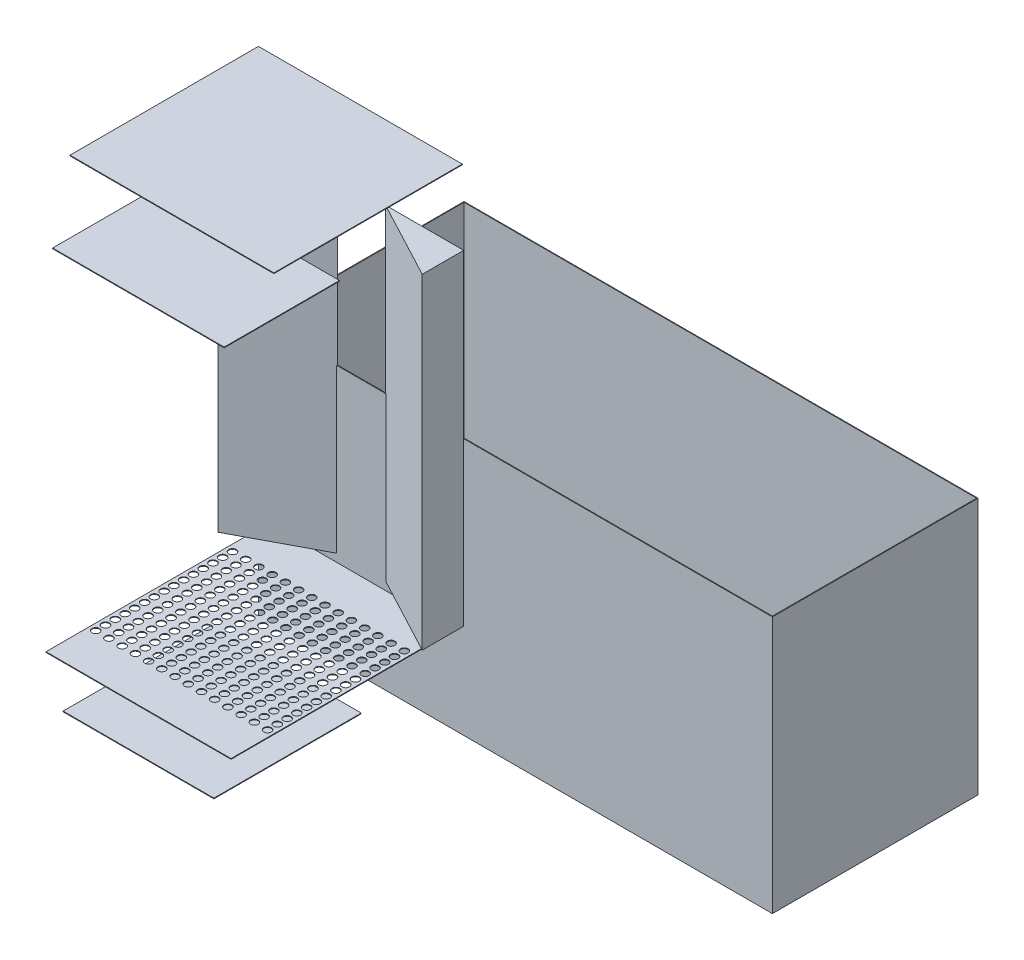
SolidWorks part; units mm, degrees
ref_plane "Спереди" through (0, 0, 0) normal (0, 0, 1) x (1, 0, 0)
ref_plane "Сверху" through (0, 0, 0) normal (0, 1, 0) x (1, 0, 0)
ref_plane "Справа" through (0, 0, 0) normal (1, 0, 0) x (0, 0, -1)
sketch "MASTER_FOOTPRINT" plane through (0, 0, 0) normal (0, 1, 0) x (1, 0, 0)
  line L1 (0, 0) -> (1500, 0)
  line L2 (0, 0) -> (0, 600)
  line L3 (0, 600) -> (1500, 600)
  line L4 (1500, 0) -> (1500, 600)
  dimension "D1" = 1500
  dimension "D2" = 600
extrude "BATH_BASE_PLATE" add sketch "MASTER_FOOTPRINT" along normal blind 750
shell "BATH_SHELL_2MM" thickness 2
sketch "Эскиз1" plane through (0, 0, 0) normal (0, 1, 0) x (1, 0, 0)
  line L1 (80, -220) -> (520, -220)
  line L2 (80, -220) -> (80, -650)
  line L3 (80, -650) -> (520, -650)
  line L4 (520, -220) -> (520, -650)
extrude "INLET_IMPACT_BAFFLE" add sketch "Эскиз1" along normal blind 2 from offset 125 separate body
sketch "Эскиз2" plane through (0, 0, 0) normal (0, 1, 0) x (1, 0, 0)
  line L0 (2, 2) -> (1498, 2) construction
  line L1 (30, 2) -> (570, 2)
  line L2 (30, 2) -> (30, -650)
  line L3 (30, -650) -> (570, -650)
  line L4 (570, 2) -> (570, -650)
  circle A0 centre (49.2857, -125) radius 11
  circle A1 centre (49.2857, -153.5) radius 11
  circle A2 centre (49.2857, -182) radius 11
  circle A3 centre (49.2857, -210.5) radius 11
  circle A4 centre (49.2857, -239) radius 11
  circle A5 centre (49.2857, -267.5) radius 11
  circle A6 centre (49.2857, -296) radius 11
  circle A7 centre (49.2857, -324.5) radius 11
  circle A8 centre (49.2857, -353) radius 11
  circle A9 centre (49.2857, -381.5) radius 11
  circle A10 centre (49.2857, -410) radius 11
  circle A11 centre (49.2857, -438.5) radius 11
  circle A12 centre (49.2857, -467) radius 11
  circle A13 centre (49.2857, -495.5) radius 11
  circle A14 centre (49.2857, -524) radius 11
  circle A15 centre (87.8571, -125) radius 11
  circle A16 centre (87.8571, -153.5) radius 11
  circle A17 centre (87.8571, -182) radius 11
  circle A18 centre (87.8571, -210.5) radius 11
  circle A19 centre (87.8571, -239) radius 11
  circle A20 centre (87.8571, -267.5) radius 11
  circle A21 centre (87.8571, -296) radius 11
  circle A22 centre (87.8571, -324.5) radius 11
  circle A23 centre (87.8571, -353) radius 11
  circle A24 centre (87.8571, -381.5) radius 11
  circle A25 centre (87.8571, -410) radius 11
  circle A26 centre (87.8571, -438.5) radius 11
  circle A27 centre (87.8571, -467) radius 11
  circle A28 centre (87.8571, -495.5) radius 11
  circle A29 centre (87.8571, -524) radius 11
  circle A30 centre (126.4286, -125) radius 11
  circle A31 centre (126.4286, -153.5) radius 11
  circle A32 centre (126.4286, -182) radius 11
  circle A33 centre (126.4286, -210.5) radius 11
  circle A34 centre (126.4286, -239) radius 11
  circle A35 centre (126.4286, -267.5) radius 11
  circle A36 centre (126.4286, -296) radius 11
  circle A37 centre (126.4286, -324.5) radius 11
  circle A38 centre (126.4286, -353) radius 11
  circle A39 centre (126.4286, -381.5) radius 11
  circle A40 centre (126.4286, -410) radius 11
  circle A41 centre (126.4286, -438.5) radius 11
  circle A42 centre (126.4286, -467) radius 11
  circle A43 centre (126.4286, -495.5) radius 11
  circle A44 centre (126.4286, -524) radius 11
  circle A45 centre (165, -125) radius 11
  circle A46 centre (165, -153.5) radius 11
  circle A47 centre (165, -182) radius 11
  circle A48 centre (165, -210.5) radius 11
  circle A49 centre (165, -239) radius 11
  circle A50 centre (165, -267.5) radius 11
  circle A51 centre (165, -296) radius 11
  circle A52 centre (165, -324.5) radius 11
  circle A53 centre (165, -353) radius 11
  circle A54 centre (165, -381.5) radius 11
  circle A55 centre (165, -410) radius 11
  circle A56 centre (165, -438.5) radius 11
  circle A57 centre (165, -467) radius 11
  circle A58 centre (165, -495.5) radius 11
  circle A59 centre (165, -524) radius 11
  circle A60 centre (203.5714, -125) radius 11
  circle A61 centre (203.5714, -153.5) radius 11
  circle A62 centre (203.5714, -182) radius 11
  circle A63 centre (203.5714, -210.5) radius 11
  circle A64 centre (203.5714, -239) radius 11
  circle A65 centre (203.5714, -267.5) radius 11
  circle A66 centre (203.5714, -296) radius 11
  circle A67 centre (203.5714, -324.5) radius 11
  circle A68 centre (203.5714, -353) radius 11
  circle A69 centre (203.5714, -381.5) radius 11
  circle A70 centre (203.5714, -410) radius 11
  circle A71 centre (203.5714, -438.5) radius 11
  circle A72 centre (203.5714, -467) radius 11
  circle A73 centre (203.5714, -495.5) radius 11
  circle A74 centre (203.5714, -524) radius 11
  circle A75 centre (242.1429, -125) radius 11
  circle A76 centre (242.1429, -153.5) radius 11
  circle A77 centre (242.1429, -182) radius 11
  circle A78 centre (242.1429, -210.5) radius 11
  circle A79 centre (242.1429, -239) radius 11
  circle A80 centre (242.1429, -267.5) radius 11
  circle A81 centre (242.1429, -296) radius 11
  circle A82 centre (242.1429, -324.5) radius 11
  circle A83 centre (242.1429, -353) radius 11
  circle A84 centre (242.1429, -381.5) radius 11
  circle A85 centre (242.1429, -410) radius 11
  circle A86 centre (242.1429, -438.5) radius 11
  circle A87 centre (242.1429, -467) radius 11
  circle A88 centre (242.1429, -495.5) radius 11
  circle A89 centre (242.1429, -524) radius 11
  circle A90 centre (280.7143, -125) radius 11
  circle A91 centre (280.7143, -153.5) radius 11
  circle A92 centre (280.7143, -182) radius 11
  circle A93 centre (280.7143, -210.5) radius 11
  circle A94 centre (280.7143, -239) radius 11
  circle A95 centre (280.7143, -267.5) radius 11
  circle A96 centre (280.7143, -296) radius 11
  circle A97 centre (280.7143, -324.5) radius 11
  circle A98 centre (280.7143, -353) radius 11
  circle A99 centre (280.7143, -381.5) radius 11
  circle A100 centre (280.7143, -410) radius 11
  circle A101 centre (280.7143, -438.5) radius 11
  circle A102 centre (280.7143, -467) radius 11
  circle A103 centre (280.7143, -495.5) radius 11
  circle A104 centre (280.7143, -524) radius 11
  circle A105 centre (319.2857, -125) radius 11
  circle A106 centre (319.2857, -153.5) radius 11
  circle A107 centre (319.2857, -182) radius 11
  circle A108 centre (319.2857, -210.5) radius 11
  circle A109 centre (319.2857, -239) radius 11
  circle A110 centre (319.2857, -267.5) radius 11
  circle A111 centre (319.2857, -296) radius 11
  circle A112 centre (319.2857, -324.5) radius 11
  circle A113 centre (319.2857, -353) radius 11
  circle A114 centre (319.2857, -381.5) radius 11
  circle A115 centre (319.2857, -410) radius 11
  circle A116 centre (319.2857, -438.5) radius 11
  circle A117 centre (319.2857, -467) radius 11
  circle A118 centre (319.2857, -495.5) radius 11
  circle A119 centre (319.2857, -524) radius 11
  circle A120 centre (357.8571, -125) radius 11
  circle A121 centre (357.8571, -153.5) radius 11
  circle A122 centre (357.8571, -182) radius 11
  circle A123 centre (357.8571, -210.5) radius 11
  circle A124 centre (357.8571, -239) radius 11
  circle A125 centre (357.8571, -267.5) radius 11
  circle A126 centre (357.8571, -296) radius 11
  circle A127 centre (357.8571, -324.5) radius 11
  circle A128 centre (357.8571, -353) radius 11
  circle A129 centre (357.8571, -381.5) radius 11
  circle A130 centre (357.8571, -410) radius 11
  circle A131 centre (357.8571, -438.5) radius 11
  circle A132 centre (357.8571, -467) radius 11
  circle A133 centre (357.8571, -495.5) radius 11
  circle A134 centre (357.8571, -524) radius 11
  circle A135 centre (396.4286, -125) radius 11
  circle A136 centre (396.4286, -153.5) radius 11
  circle A137 centre (396.4286, -182) radius 11
  circle A138 centre (396.4286, -210.5) radius 11
  circle A139 centre (396.4286, -239) radius 11
  circle A140 centre (396.4286, -267.5) radius 11
  circle A141 centre (396.4286, -296) radius 11
  circle A142 centre (396.4286, -324.5) radius 11
  circle A143 centre (396.4286, -353) radius 11
  circle A144 centre (396.4286, -381.5) radius 11
  circle A145 centre (396.4286, -410) radius 11
  circle A146 centre (396.4286, -438.5) radius 11
  circle A147 centre (396.4286, -467) radius 11
  circle A148 centre (396.4286, -495.5) radius 11
  circle A149 centre (396.4286, -524) radius 11
  circle A150 centre (435, -125) radius 11
  circle A151 centre (435, -153.5) radius 11
  circle A152 centre (435, -182) radius 11
  circle A153 centre (435, -210.5) radius 11
  circle A154 centre (435, -239) radius 11
  circle A155 centre (435, -267.5) radius 11
  circle A156 centre (435, -296) radius 11
  circle A157 centre (435, -324.5) radius 11
  circle A158 centre (435, -353) radius 11
  circle A159 centre (435, -381.5) radius 11
  circle A160 centre (435, -410) radius 11
  circle A161 centre (435, -438.5) radius 11
  circle A162 centre (435, -467) radius 11
  circle A163 centre (435, -495.5) radius 11
  circle A164 centre (435, -524) radius 11
  circle A165 centre (473.5714, -125) radius 11
  circle A166 centre (473.5714, -153.5) radius 11
  circle A167 centre (473.5714, -182) radius 11
  circle A168 centre (473.5714, -210.5) radius 11
  circle A169 centre (473.5714, -239) radius 11
  circle A170 centre (473.5714, -267.5) radius 11
  circle A171 centre (473.5714, -296) radius 11
  circle A172 centre (473.5714, -324.5) radius 11
  circle A173 centre (473.5714, -353) radius 11
  circle A174 centre (473.5714, -381.5) radius 11
  circle A175 centre (473.5714, -410) radius 11
  circle A176 centre (473.5714, -438.5) radius 11
  circle A177 centre (473.5714, -467) radius 11
  circle A178 centre (473.5714, -495.5) radius 11
  circle A179 centre (473.5714, -524) radius 11
  circle A180 centre (512.1429, -125) radius 11
  circle A181 centre (512.1429, -153.5) radius 11
  circle A182 centre (512.1429, -182) radius 11
  circle A183 centre (512.1429, -210.5) radius 11
  circle A184 centre (512.1429, -239) radius 11
  circle A185 centre (512.1429, -267.5) radius 11
  circle A186 centre (512.1429, -296) radius 11
  circle A187 centre (512.1429, -324.5) radius 11
  circle A188 centre (512.1429, -353) radius 11
  circle A189 centre (512.1429, -381.5) radius 11
  circle A190 centre (512.1429, -410) radius 11
  circle A191 centre (512.1429, -438.5) radius 11
  circle A192 centre (512.1429, -467) radius 11
  circle A193 centre (512.1429, -495.5) radius 11
  circle A194 centre (512.1429, -524) radius 11
  circle A195 centre (550.7143, -125) radius 11
  circle A196 centre (550.7143, -153.5) radius 11
  circle A197 centre (550.7143, -182) radius 11
  circle A198 centre (550.7143, -210.5) radius 11
  circle A199 centre (550.7143, -239) radius 11
  circle A200 centre (550.7143, -267.5) radius 11
  circle A201 centre (550.7143, -296) radius 11
  circle A202 centre (550.7143, -324.5) radius 11
  circle A203 centre (550.7143, -353) radius 11
  circle A204 centre (550.7143, -381.5) radius 11
  circle A205 centre (550.7143, -410) radius 11
  circle A206 centre (550.7143, -438.5) radius 11
  circle A207 centre (550.7143, -467) radius 11
  circle A208 centre (550.7143, -495.5) radius 11
  circle A209 centre (550.7143, -524) radius 11
extrude "DISTRIBUTOR_D22" add sketch "Эскиз2" along normal blind 2 from offset 250 separate body
sketch "Эскиз3" plane through (0, 0, 0) normal (0, 1, 0) x (1, 0, 0)
  line L0 (30, -650) -> (570, -650) construction
  line L1 (49.2857, -313.5) -> (550, -313.5)
  line L2 (49.2857, -313.5) -> (49.2857, -650)
  line L3 (49.2857, -650) -> (550, -650)
  line L4 (550, -313.5) -> (550, -650)
  circle A0 centre (49.2857, -324.5) radius 11 construction
extrude "OUTLET_SUBMERGED_BAFFLE" add sketch "Эскиз3" along normal blind 2 from offset 1280 separate body
sketch "Эскиз4" plane through (0, 0, 0) normal (0, 1, 0) x (1, 0, 0)
  line L1 (0, 0) -> (595, 0)
  line L2 (0, 0) -> (0, -550)
  line L3 (0, -550) -> (595, -550)
  line L4 (595, 0) -> (595, -550)
extrude "OVERFLOW_WEIR_Z550" add sketch "Эскиз4" along normal blind 2 from offset 1440 separate body
sketch "Эскиз5" plane through (0, 0, 0) normal (0, 1, 0) x (1, 0, 0)
  line L0 (2, 1) -> (2, -120)
  line L1 (2, -120) -> (230, 1)
  line L2 (230, 1) -> (2, 1)
  line L3 (598, 1) -> (598, -120)
  line L4 (598, -120) -> (370, 1)
  line L5 (370, 1) -> (598, 1)
extrude "SLOPED_SEDIMENT_FLOOR" add sketch "Эскиз5" along normal blind 950 from offset 275
sketch3d "SCREW_AXIS_30DEG_REFERENCE"
  line L0 (300, 400, 70) -> (300, 1600, 762.8203)
equation "\"AI_Q_Peak\"= 0.006"
equation "\"AI_B_Bath\" = 600"
equation "\"AI_L_Settle\" = 1050"
equation "\"AI_L_Inlet\"= 250"
equation "\"AI_L_Outlet\"= 200"
equation "\"AI_L_Bath\" = 1500"
equation "\"AI_H_Water\"= 550"
equation "\"AI_H_Freeboard\"= 200"
equation "\"AI_H_Bath\"= 750"
equation "\"AI_Shell_Thickness\"= 2"
equation "\"AI_Inlet_DN\"= 100"
equation "\"AI_Weir_Width\"= 600"
equation "\"AI_Inlet_Baffle_Offset\"= 125"
equation "\"AI_Distributor_Open_Area\"= 0.28"
equation "\"AI_Distributor_Hole_Dia\"= 22"
equation "\"AI_Distributor_Blind_Zone\"= 110"
equation "\"AI_Outlet_Baffle_Depth\"= 250"
equation "\"AI_Screw_Diameter\"= 100"
equation "\"AI_Screw_Pitch\"= 100"
equation "\"AI_Screw_Angle\"= 30"
equation "\"AI_Screw_Rpm\"= 15"
equation "\"AI_Screw_Clearance\"= 5"
equation "\"AI_Liner_Thickness\"= 5"
equation "\"AI_Discharge_Height\"= 650"
equation "\"AI_Frame_Height\"= 500"
equation "\"D1@MASTER_FOOTPRINT\" = \"AI_L_Bath\""
equation "\"D2@MASTER_FOOTPRINT\" = \"AI_B_Bath\""
equation "\"D1@BATH_BASE_PLATE\" = \"AI_H_Bath\""
